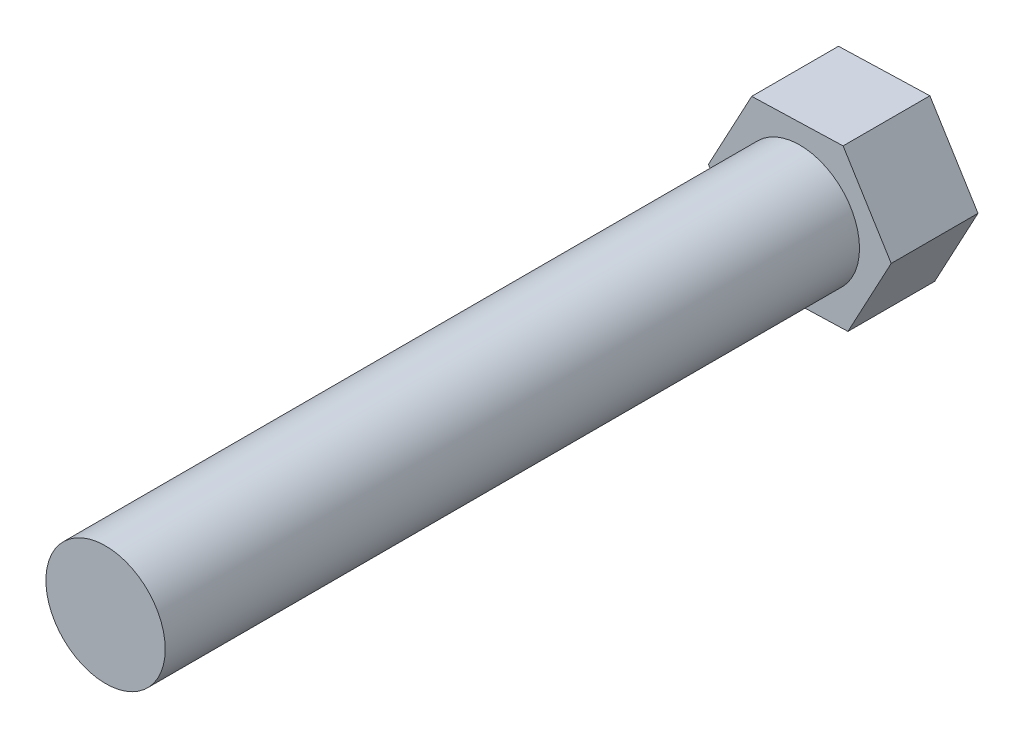
SolidWorks part; units mm, degrees
ref_plane "Front Plane" through (0, 0, 0) normal (0, 0, 1) x (1, 0, 0)
ref_plane "Top Plane" through (0, 0, 0) normal (0, 1, 0) x (1, 0, 0)
ref_plane "Right Plane" through (0, 0, 0) normal (1, 0, 0) x (0, 0, -1)
sketch "Sketch1" plane through (0, 0, 0) normal (0, 0, 1) x (1, 0, 0)
  circle A0 centre (0, 0) radius 2.75
  dimension "D1" = 5.5
extrude "Boss-Extrude1" add sketch "Sketch1" along normal blind 32
sketch "Sketch2" plane through (0, 0, 0) normal (0, 0, -1) x (-1, 0, 0)
  line L1 (1.9942, -3.7122) -> (4.212, -0.1291)
  line L2 (4.212, -0.1291) -> (2.2178, 3.5832)
  line L3 (2.2178, 3.5832) -> (-1.9942, 3.7122)
  line L4 (-1.9942, 3.7122) -> (-4.212, 0.1291)
  line L5 (-4.212, 0.1291) -> (-2.2178, -3.5832)
  line L6 (-2.2178, -3.5832) -> (1.9942, -3.7122)
  circle A0 centre (0, 0) radius 3.6494 construction
extrude "Boss-Extrude2" add sketch "Sketch2" along normal blind 4
